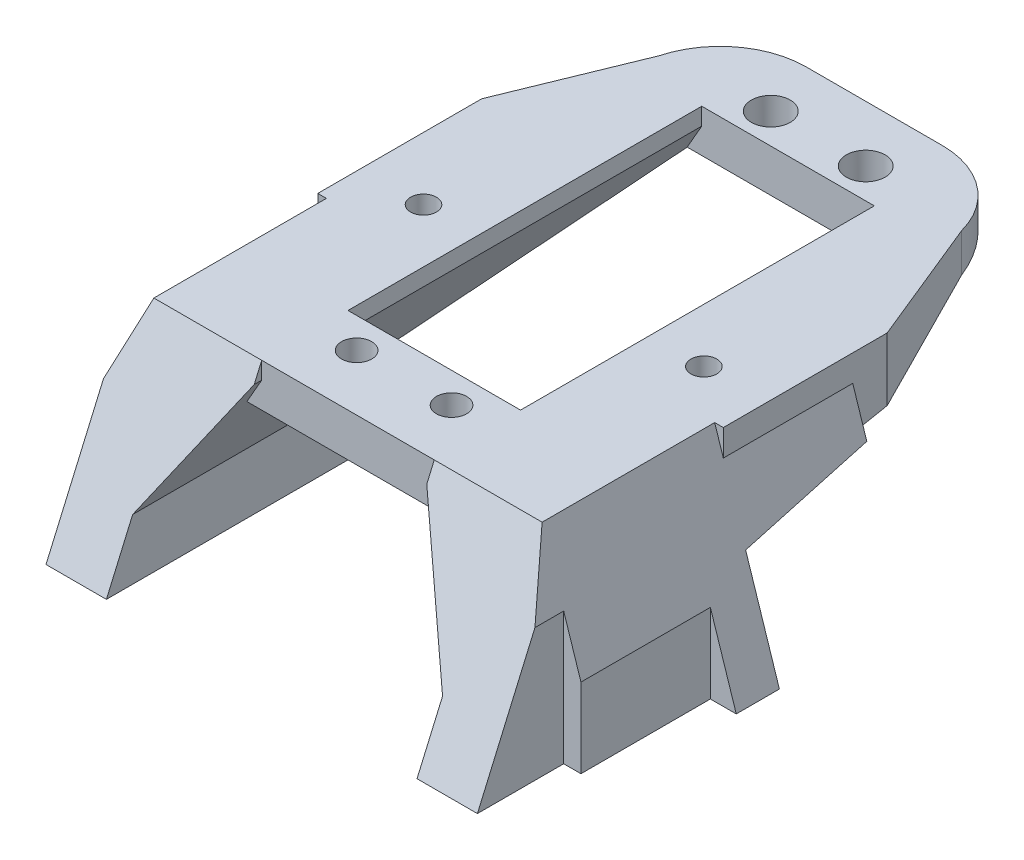
SolidWorks part; units mm, degrees
ref_plane "Alzado" through (0, 0, 0) normal (0, 0, 1) x (1, 0, 0)
ref_plane "Planta" through (0, 0, 0) normal (0, 1, 0) x (1, 0, 0)
ref_plane "Vista lateral" through (0, 0, 0) normal (1, 0, 0) x (0, 0, -1)
sketch "Croquis1" plane through (0, 0, 0) normal (0, 0, 1) x (1, 0, 0)
  line L0 (0, 0) -> (45, 0)
  line L1 (0, 0) -> (-7.5, -23)
  line L2 (-7.5, -23) -> (4.5, -23)
  line L3 (52.5, -23) -> (45, 0)
  line L4 (22.5, 0) -> (22.5, -26.8695) construction
  line L5 (12.5, -2) -> (32.5, -2)
  line L8 (40.5, -23) -> (52.5, -23)
  line L9 (4.5, -23) -> (4.5, -16)
  line L11 (40.5, -16.1924) -> (40.5, -23)
  line L12 (4.5, -16) -> (12.5, -2)
  line L13 (40.5, -16.1924) -> (32.5, -2)
  dimension "D1" = 45
  dimension "D2" = 30
  dimension "D3" = 30
  dimension "D5" = 18
  dimension "D6" = 18
  dimension "D7" = 23
  dimension "D8" = 20
  dimension "D4" = 21
  dimension "D9" = 10
  dimension "D10" = 7
extrude "Saliente-Extruir1" add sketch "Croquis1" along normal blind 35
sketch "Croquis6" plane through (0, 0, 0) normal (0, 1, 0) x (1, 0, 0)
  line L0 (45, 0) -> (0, 0) construction
  line L1 (12.5, 0) -> (32.5, 0)
  line L2 (12.5, 0) -> (12.5, -25)
  line L3 (12.5, -25) -> (32.5, -25)
  line L4 (32.5, 0) -> (32.5, -25)
  line L5 (45, -35) -> (0, -35) construction
  line L6 (0, -35) -> (0, 0) construction
  line L7 (22.5, -25) -> (22.5, -41.101) construction
  circle A0 centre (17, -28.5) radius 2.25
  circle A1 centre (28, -28.5) radius 2.25
  point P12 (22.5, -35)
  dimension "D6" = 4.5
  dimension "D1" = 12.5
  dimension "D2" = 10
  dimension "D3" = 3.5
  dimension "D4" = 20
  dimension "D5" = 4.5
extrude "Cortar-Extruir3" cut sketch "Croquis6" against normal blind 10
sketch "Croquis7" plane through (0, 0, 0) normal (0, 1, 0) x (1, 0, 0)
  line L0 (12.5, 0) -> (12.5, 16) construction
  line L1 (32.5, 0) -> (32.5, 16) construction
  line L2 (12.5, 16) -> (32.5, 16)
  line L3 (12.5, -25) -> (32.5, -25) construction
  line L4 (14.6178, 26) -> (30.3822, 26)
  line L5 (22.5, 16) -> (22.5, 41.3) construction
  line L6 (4.9557, 18.5775) -> (0, 0)
  line L7 (40.0443, 18.5775) -> (45, 0)
  line L8 (12.5, 16) -> (12.5, 0)
  line L9 (12.5, 0) -> (0, 0)
  line L10 (32.5, 16) -> (32.5, 0)
  line L11 (32.5, 0) -> (45, 0)
  line L12 (12.5, -4.5) -> (32.5, -4.5) construction
  line L13 (12.5, 0) -> (12.5, -25) construction
  line L14 (32.5, -25) -> (32.5, 0) construction
  arc A0 (14.6178, 26) -> (4.9557, 18.5775) centre (14.6178, 16) ccw
  arc A1 (30.3822, 26) -> (40.0443, 18.5775) centre (30.3822, 16) cw
  circle A2 centre (17, -28.5) radius 2.25 construction
  circle A3 centre (28, -28.5) radius 2.25 construction
  circle A6 centre (28, 19.5) radius 2.25
  circle A7 centre (17, 19.5) radius 2.25
  point P6 (22.5, -25)
  point P18 (22.5, 26)
  dimension "D3" = 10
  dimension "D1" = 41
  dimension "D2" = 10
  dimension "D4" = 20.5
extrude "Saliente-Extruir4" add sketch "Croquis7" against normal blind 15 separate body
sketch "Croquis8" plane through (0, -23, 0) normal (0, -1, 0) x (-1, 0, 0)
  line L0 (-12.5, -25) -> (-32.5, -25) construction
  line L1 (-22.5, -35) -> (-22.5, -13.0658) construction
  line L2 (-12.5, -35) -> (-32.5, -35) construction
  circle A0 centre (-2.5, -33.3) radius 1.5
  circle A1 centre (-42.5, -33.3) radius 1.5
  dimension "D2" = 3
  dimension "D1" = 8.3
  dimension "D3" = 20
extrude "Cortar-Extruir4" cut sketch "Croquis8" against normal blind 10
sketch "Croquis10" plane through (0, 0, 0) normal (1, 0, 0) x (0, 0, -1)
  line L0 (0, -15) -> (26, -3)
  line L1 (26, -15) -> (26, 0) construction
  line L2 (26, -3) -> (26, 0)
  line L3 (26, 0) -> (28.245, 0)
  line L4 (28.245, 0) -> (28.245, -21.8561)
  line L5 (28.245, -21.8561) -> (0, -15)
  dimension "D1" = 3
extrude "Cortar-Extruir8" cut sketch "Croquis10" along normal blind 50
sketch "Croquis11" plane through (0, -23, 0) normal (0, -1, 0) x (1, 0, 0)
  line L0 (-7.5, 35) -> (-7.5, 0) construction
  line L5 (52.5, 35) -> (52.5, 0) construction
  line L6 (-7.5, 15) -> (-7.5, -3.0306)
  line L7 (-7.5, -3.0306) -> (52.5, -3.0306)
  line L8 (52.5, -3.0306) -> (52.5, 15)
  line L9 (-7.5, 35) -> (4.5, 35) construction
  line L10 (40.5, 35) -> (52.5, 35) construction
  arc A0 (-7.5, 15) -> (52.5, 15) centre (22.5, 57.9128) ccw
  dimension "D1" = 20
  dimension "D2" = 20
extrude "Cortar-Extruir11" cut sketch "Croquis11" against normal up to surface (1.0769 mm away)
sketch "Croquis12" plane through (0, 0, 0) normal (0, 0, 1) x (1, 0, 0)
  line L0 (22.5, 0) -> (22.5, -24.5967) construction
  line L1 (45, 0) -> (0, 0) construction
  line L2 (12.5, -2) -> (12.5, -7.5)
  line L4 (12.5, -2) -> (0.8852, -22.326)
  line L5 (4.5, -16) -> (12.5, -2) construction
  line L6 (0.8852, -22.326) -> (12.5, -22.326)
  line L7 (12.5, -22.326) -> (12.5, -7.5)
  line L8 (12.5, -15) -> (12.5, 0) construction
  line L9 (44.1148, -22.326) -> (32.5, -22.326)
  line L11 (32.5, -2) -> (44.1148, -22.326)
  line L12 (32.5, -2) -> (32.5, -7.5)
  line L13 (32.5, -22.326) -> (32.5, -7.5)
extrude "Cortar-Extruir12" cut sketch "Croquis12" against normal up to surface (16 mm away) up to face at (22.5, -3.8077, -16)
sketch "Croquis13" plane through (0, 0, 35) normal (0, 0, 1) x (1, 0, 0)
  line L0 (22.5, 0) -> (22.5, -30.4175) construction
  line L1 (45, 0) -> (0, 0) construction
  line L2 (-7.5, -23) -> (4.5, -23) construction
  line L3 (-4.5, -23) -> (-10.5813, -23)
  line L4 (-4.5, -23) -> (-4.5, -13.2462)
  line L5 (-4.5, -13.2462) -> (-10.5813, -13.2462)
  line L6 (-10.5813, -23) -> (-10.5813, -13.2462)
  line L7 (49.5, -23) -> (55.5813, -23)
  line L8 (49.5, -13.2462) -> (55.5813, -13.2462)
  line L9 (49.5, -23) -> (49.5, -13.2462)
  line L10 (55.5813, -23) -> (55.5813, -13.2462)
  dimension "D1" = 27
extrude "Cortar-Extruir13" cut sketch "Croquis13" against normal blind 15
sketch "Croquis14" plane through (0, 0, 0) normal (1, 0, 0) x (0, 0, -1)
  line L0 (-15, -11) -> (-15, -28.8588)
  line L1 (-15, -11) -> (26, -3)
  line L2 (-35, -13.8) -> (-35, -23) construction
  line L4 (26, -23) -> (26, -3)
  line L6 (-15, -28.8588) -> (26, -23)
  dimension "D1" = 20
extrude "Cortar-Extruir14" cut sketch "Croquis14" along normal mid plane 127
sketch "Croquis15" plane through (0, 0, 0) normal (1, 0, 0) x (0, 0, -1)
  line L0 (-15, -23) -> (-15, -11)
  line L1 (-15, -11) -> (26, -3)
  line L2 (26, -3) -> (-15, -23)
extrude "Cortar-Extruir15" cut sketch "Croquis15" against normal mid plane 200
sketch "Croquis16" plane through (0, -23, 0) normal (0, -1, 0) x (1, 0, 0)
  line L0 (22.5, 35) -> (22.5, 51.8093) construction
  line L1 (12.5, 35) -> (-2.5, 35)
  line L2 (12.5, 35) -> (12.5, 45)
  line L3 (12.5, 45) -> (-2.5, 45)
  line L4 (-2.5, 35) -> (-2.5, 45)
  line L5 (12.5, 35) -> (32.5, 35) construction
  line L6 (32.5, 35) -> (47.5, 35)
  line L7 (32.5, 35) -> (32.5, 45)
  line L8 (32.5, 45) -> (47.5, 45)
  line L9 (47.5, 35) -> (47.5, 45)
  dimension "D1" = 15
  dimension "D2" = 10
extrude "Saliente-Extruir5" add sketch "Croquis16" against normal up to surface (23 mm away) up to face at (30.25, 0, 28.5)
sketch "Croquis17" plane through (-2.5, 0, 0) normal (-1, 0, 0) x (0, 0, 1)
  line L0 (35, 0) -> (45, -23)
  line L1 (45, -23) -> (45, 0)
  line L2 (45, 0) -> (35, 0)
extrude "Cortar-Extruir16" cut sketch "Croquis17" against normal blind 200
sketch "Croquis18" plane through (0, 0, 35) normal (0, 0, -1) x (-1, 0, 0)
  line L0 (-32.5, -2) -> (-40.5, -16.1924) construction
  line L1 (-40.5, -16.1924) -> (-40.5, -23) construction
  line L2 (-40.5, -23) -> (-32.5, -23) construction
  line L3 (-32.5, -23) -> (-32.5, -2) construction
  line L4 (-12.5, -23) -> (-4.5, -23) construction
  line L5 (-4.5, -23) -> (-4.5, -16) construction
  line L6 (-4.5, -16) -> (-12.5, -2) construction
  line L7 (-12.5, -2) -> (-12.5, -23) construction
  line L8 (-32.5, -2) -> (-40.5, -16.1924)
  line L9 (-40.5, -16.1924) -> (-40.5, -23)
  line L10 (-40.5, -23) -> (-32.5, -23)
  line L11 (-32.5, -23) -> (-32.5, -2)
  line L12 (-12.5, -23) -> (-4.5, -23)
  line L13 (-4.5, -23) -> (-4.5, -16)
  line L14 (-4.5, -16) -> (-12.5, -2)
  line L15 (-12.5, -2) -> (-12.5, -23)
  line L16 (-47.5, -7.6667) -> (-45, 0) construction
  line L17 (-45, 0) -> (-47.5, 0) construction
  line L18 (-47.5, 0) -> (-47.5, -7.6667) construction
  line L19 (2.5, 0) -> (0, 0) construction
  line L20 (0, 0) -> (2.5, -7.6667) construction
  line L21 (2.5, -7.6667) -> (2.5, 0) construction
  line L22 (-47.5, -7.6667) -> (-45, 0)
  line L23 (-45, 0) -> (-47.5, 0)
  line L24 (-47.5, 0) -> (-47.5, -7.6667)
  line L25 (2.5, 0) -> (0, 0)
  line L26 (0, 0) -> (2.5, -7.6667)
  line L27 (2.5, -7.6667) -> (2.5, 0)
extrude "Cortar-Extruir17" cut sketch "Croquis18" against normal blind 200
ref_plane "Plano1" through (22.5, 0, 0) normal (1, 0, 0) x (0, 0, -1)
sketch "Croquis20" plane through (22.5, 0, 0) normal (1, 0, 0) x (0, 0, -1)
  line L0 (-15, -11) -> (-15, 0)
  line L1 (-15, 0) -> (26, 0)
  line L2 (26, 0) -> (26, -3)
  line L3 (26, -3) -> (-15, -11)
sketch "Croquis22" plane through (0, 0, 0) normal (0, 1, 0) x (1, 0, 0)
  line L0 (12.5, 0) -> (12.5, -25)
  line L1 (12.5, 0) -> (12.5, 16) construction
  line L2 (12.5, 16) -> (32.5, 16) construction
  line L3 (32.5, 16) -> (32.5, 0) construction
  line L4 (12.5, -25) -> (32.5, -25)
  line L5 (32.5, 0) -> (32.5, -25)
  line L6 (30.3822, 26) -> (14.6178, 26) construction
  line L18 (4.9557, 18.5775) -> (-2.6326, 0)
  line L19 (12.5, 0) -> (12.5, 16)
  line L20 (12.5, 16) -> (32.5, 16)
  line L21 (32.5, 16) -> (32.5, 0)
  line L22 (0, 31.2575) -> (45, 31.2575)
  line L24 (30.3822, 26) -> (14.6178, 26)
  line L26 (47.6326, 0) -> (40.0443, 18.5775)
  line L27 (0, 31.2575) -> (-11.6885, 31.2575)
  line L28 (-11.6885, 31.2575) -> (-11.6885, 0)
  line L29 (-2.6326, 0) -> (-11.6885, 0)
  line L30 (47.6326, 0) -> (58.8739, 0)
  line L31 (58.8739, 0) -> (54.897, 31.2575)
  line L33 (54.897, 31.2575) -> (45, 31.2575)
  arc A0 (40.0443, 18.5775) -> (30.3822, 26) centre (30.3822, 16) ccw construction
  arc A1 (14.6178, 26) -> (4.9557, 18.5775) centre (14.6178, 16) ccw construction
  arc A2 (40.0443, 18.5775) -> (30.3822, 26) centre (30.3822, 16) ccw
  arc A3 (14.6178, 26) -> (4.9557, 18.5775) centre (14.6178, 16) ccw
  circle A4 centre (17, 19.5) radius 2.25 construction
  circle A5 centre (28, 19.5) radius 2.25 construction
  circle A6 centre (17, 19.5) radius 2.25
  circle A7 centre (28, 19.5) radius 2.25
extrude "Saliente-Extruir7" add sketch "Croquis20" along normal mid plane 47
extrude "Cortar-Extruir19" cut sketch "Croquis22" against normal blind 47
sketch "Croquis23" plane through (0, 0, 15) normal (0, 0, 1) x (1, 0, 0)
  line L0 (7.3571, -11) -> (12.5, -11) construction
  line L1 (12.5, -11) -> (12.5, -2) construction
  line L2 (12.5, -2) -> (7.3571, -11) construction
  line L3 (37.5731, -11) -> (32.5, -2) construction
  line L4 (32.5, -2) -> (32.5, -11) construction
  line L5 (32.5, -11) -> (37.5731, -11) construction
  line L6 (7.3571, -11) -> (12.5, -11)
  line L7 (12.5, -11) -> (12.5, -2)
  line L8 (12.5, -2) -> (7.3571, -11)
  line L9 (37.5731, -11) -> (32.5, -2)
  line L10 (32.5, -2) -> (32.5, -11)
  line L11 (32.5, -11) -> (37.5731, -11)
extrude "Cortar-Extruir20" cut sketch "Croquis23" against normal up to surface (31 mm away) up to face at (22.5, -2.4756, -16)
sketch "Croquis24" plane through (0, 0, 35) normal (0, 0, 1) x (1, 0, 0)
  line L0 (12.5, 0) -> (0, 0) construction
  line L1 (8.1743, 0) -> (37.5948, 0)
  line L2 (8.1743, 0) -> (8.1743, -5)
  line L3 (8.1743, -5) -> (37.5948, -5)
  line L4 (37.5948, 0) -> (37.5948, -5)
  dimension "D1" = 5
extrude "Saliente-Extruir9" add sketch "Croquis24" against normal blind 10
sketch "Croquis25" plane through (0, 0, 0) normal (0, 1, 0) x (1, 0, 0)
  line L0 (22.5, -25) -> (22.5, -45.2044) construction
  line L1 (12.5, -35) -> (0, -35) construction
  circle A0 centre (17, -28.5) radius 1.75
  circle A1 centre (28, -28.5) radius 1.75
  circle A2 centre (6.253, -10) radius 1.5
  circle A3 centre (38.747, -10) radius 1.5
  point P10 (6.25, -35)
  dimension "D1" = 3.5
  dimension "D2" = 3
  dimension "D3" = 25
extrude "Cortar-Extruir21" cut sketch "Croquis25" against normal blind 5
